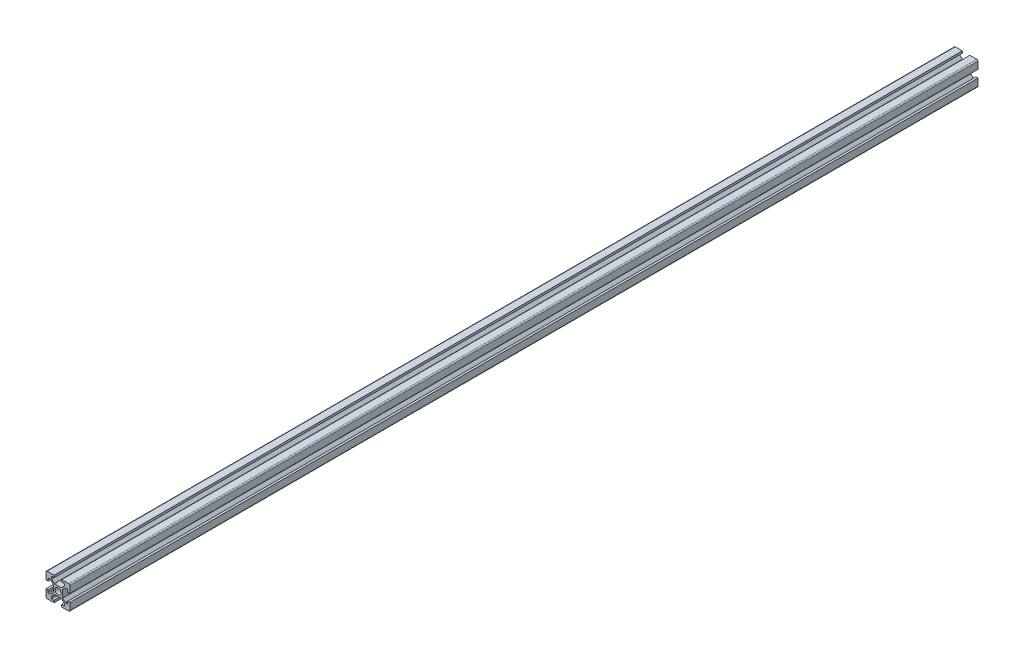
SolidWorks part; units mm, degrees
material "1060 Alloy"
ref_plane "Front Plane" through (0, 0, 0) normal (0, 0, 1) x (1, 0, 0)
ref_plane "Top Plane" through (0, 0, 0) normal (0, 1, 0) x (1, 0, 0)
ref_plane "Right Plane" through (0, 0, 0) normal (1, 0, 0) x (0, 0, -1)
sketch "Sketch1" plane through (0, 0, 0) normal (0, 0, 1) x (1, 0, 0)
  line L0 (20, 0) -> (-8.059, 28.059) construction
  line L1 (0, 0) -> (6.8, 0)
  line L2 (0, 0) -> (0, 6.8)
  line L3 (0, 20) -> (6.8, 20)
  line L4 (20, 0) -> (20, 6.8)
  line L5 (6.8, 20) -> (6.8, 18.2)
  line L6 (20, 20) -> (8.2322, 8.2322) construction
  line L7 (12.95, 6.1) -> (7.05, 6.1)
  line L8 (13.9, 7.05) -> (13.9, 12.95)
  line L9 (12.95, 13.9) -> (7.05, 13.9)
  line L10 (6.1, 7.05) -> (6.1, 12.95)
  line L11 (13.9, 6.1) -> (6.1, 13.9) construction
  line L12 (13.9, 13.9) -> (6.1, 6.1) construction
  line L13 (4.55, 16.4) -> (7.05, 13.9)
  line L14 (13.2, 18.2) -> (13.2, 20)
  line L15 (1.8, 6.8) -> (0, 6.8)
  line L16 (0, 13.2) -> (0, 20)
  line L17 (0, 13.2) -> (1.8, 13.2)
  line L18 (10, 10) -> (10, 13.9) construction
  line L19 (16.4, 4.55) -> (13.9, 7.05)
  line L20 (4.55, 16.4) -> (4.55, 18.2)
  line L21 (4.55, 18.2) -> (6.8, 18.2)
  line L22 (13.2, 18.2) -> (15.45, 18.2)
  line L23 (15.45, 18.2) -> (15.45, 16.4)
  line L24 (15.45, 16.4) -> (12.95, 13.9)
  line L25 (16.4, 4.55) -> (18.2, 4.55)
  line L26 (18.2, 4.55) -> (18.2, 6.8)
  line L27 (20, 6.8) -> (18.2, 6.8)
  line L28 (18.2, 13.2) -> (20, 13.2)
  line L29 (18.2, 13.2) -> (18.2, 15.45)
  line L30 (18.2, 15.45) -> (16.4, 15.45)
  line L31 (16.4, 15.45) -> (13.9, 12.95)
  line L32 (1.8, 4.55) -> (3.6, 4.55)
  line L33 (3.6, 15.45) -> (6.1, 12.95)
  line L34 (3.6, 15.45) -> (1.8, 15.45)
  line L35 (1.8, 15.45) -> (1.8, 13.2)
  line L36 (0, 13.2) -> (1.8, 13.2)
  line L37 (1.8, 6.8) -> (0, 6.8)
  line L38 (3.6, 4.55) -> (6.1, 7.05)
  line L39 (1.8, 6.8) -> (1.8, 4.55)
  line L40 (15.45, 3.6) -> (12.95, 6.1)
  line L41 (4.55, 3.6) -> (7.05, 6.1)
  line L42 (4.55, 1.8) -> (4.55, 3.6)
  line L43 (6.8, 1.8) -> (4.55, 1.8)
  line L44 (6.8, 1.8) -> (6.8, 0)
  line L45 (15.45, 3.6) -> (15.45, 1.8)
  line L46 (15.45, 1.8) -> (13.2, 1.8)
  line L47 (13.2, 0) -> (13.2, 1.8)
  line L48 (13.2, 20) -> (20, 20)
  line L49 (20, 13.2) -> (20, 20)
  line L50 (13.2, 0) -> (20, 0)
  line L51 (6.1, 6.1) -> (-5.5045, -5.5045) construction
  circle A0 centre (10, 10) radius 2.5
  point P25 (10, 16.4)
  point P39 (13.2, 19.1)
  point P46 (0.9, 6.8)
  dimension "D3" = 5
  dimension "D2" = 20
  dimension "D4" = 7.8
  dimension "D5" = 7.8
  dimension "D6" = 6.8
  dimension "D7" = 6.8
  dimension "D8" = 1.8
  dimension "D9" = 10.9
  dimension "D10" = 1.8
  dimension "D11" = 10.9
  dimension "D12" = 20
extrude "Boss-Extrude1" add sketch "Sketch1" along normal blind 762 contours L47 L50 L4 L27 L26 L25 L19 L8 L31 L30 L29 L28 L49 L48 L14 L22 L23 L24 L9 L13 L20 L21 L5 L3 L16 L17 L35 L34 L33 L10 L38 L32 L39 L15 L2 L1 L44 L43 L42 L41 L7 L40 L45 L46 A0
fillet "Fillet1" radius 1 4 edges at (20, 20, 381) (20, 0, 381) (0, 0, 381) (0, 20, 381)
fillet "Fillet2" radius 0.5 6 edges at (4.55, 18.2, 381) (4.55, 16.4, 381) (7.05, 13.9, 381) (15.45, 18.2, 381) (15.45, 16.4, 381) (12.95, 13.9, 381)
fillet "Fillet3" radius 0.5 6 edges at (18.2, 15.45, 381) (16.4, 15.45, 381) (13.9, 12.95, 381) (18.2, 4.55, 381) (13.9, 7.05, 381) (16.4, 4.55, 381)
fillet "Fillet4" radius 0.5 6 edges at (1.8, 15.45, 381) (3.6, 15.45, 381) (6.1, 12.95, 381) (3.6, 4.55, 381) (1.8, 4.55, 381) (6.1, 7.05, 381)
fillet "Fillet5" radius 0.5 6 edges at (7.05, 6.1, 381) (4.55, 3.6, 381) (4.55, 1.8, 381) (15.45, 1.8, 381) (15.45, 3.6, 381) (12.95, 6.1, 381)
